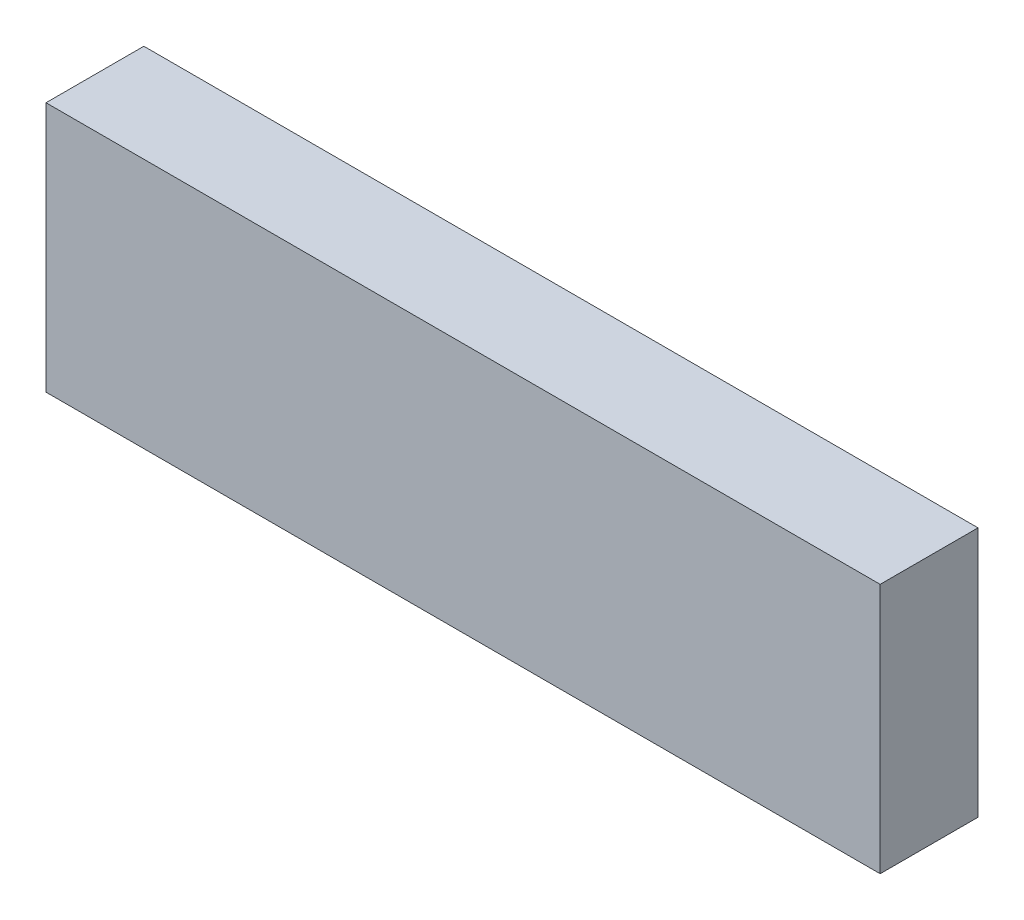
SolidWorks part; units mm, degrees
ref_plane "Front Plane" through (0, 0, 0) normal (0, 0, 1) x (1, 0, 0)
ref_plane "Top Plane" through (0, 0, 0) normal (0, 1, 0) x (1, 0, 0)
ref_plane "Right Plane" through (0, 0, 0) normal (1, 0, 0) x (0, 0, -1)
sketch "Sketch1" plane through (0, 0, 0) normal (0, 0, 1) x (1, 0, 0)
  line L4 (-20.3, 0) -> (20.3, 0)
  line L5 (20.3, 0) -> (20.3, 12.2)
  line L6 (20.3, 12.2) -> (-20.3, 12.2)
  line L7 (-20.3, 12.2) -> (-20.3, 0)
  line L8 (-20.3, 0) -> (20.3, 0)
  line L9 (20.3, 0) -> (20.3, 12.2)
  line L10 (20.3, 12.2) -> (-20.3, 12.2)
  line L11 (-20.3, 12.2) -> (-20.3, 0)
  dimension "D1" = 0
extrude "Boss-Extrude1" add sketch "Sketch1" along normal blind 4.7625
